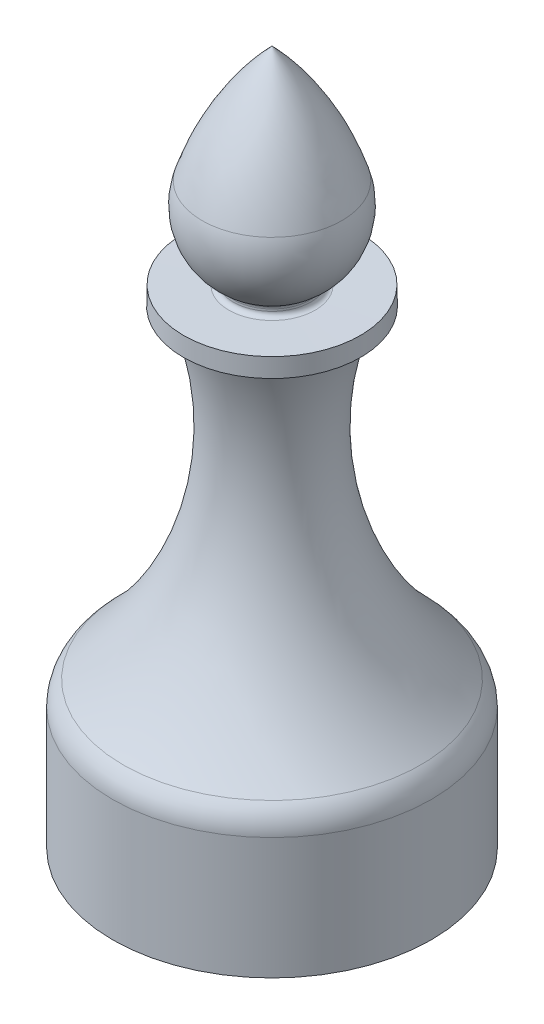
SolidWorks part; units mm, degrees
ref_plane "Front Plane" through (0, 0, 0) normal (0, 0, 1) x (1, 0, 0)
ref_plane "Top Plane" through (0, 0, 0) normal (0, 1, 0) x (1, 0, 0)
ref_plane "Right Plane" through (0, 0, 0) normal (1, 0, 0) x (0, 0, -1)
sketch "Sketch1" plane through (0, 0, 0) normal (0, 0, 1) x (1, 0, 0)
  line L0 (-45.1214, 61) -> (64.5343, 61) construction
  line L1 (0, 0) -> (14, 0)
  line L7 (0, 61) -> (0, 0)
  line L8 (14, 0) -> (14, 12)
  line L9 (0, 27.1439) -> (8.5958, 14.8679)
  line L10 (9.5, 12) -> (9.5, 0)
  line L11 (9.5, 12) -> (14, 12) construction
  arc A0 (14, 6.8598) -> (6.1449, 40.3453) centre (37.7288, 30.0902) cw construction
  arc A5 (6.1449, 40.3453) -> (14, 12) centre (31.4966, 32.1097) ccw
  arc A6 (8.5958, 14.8679) -> (9.5, 12) centre (4.5, 12) cw
  point P29 (9.5, 13.5765)
  line B0 (6.1449, 40.3453) -> (7.7914, 41.2078)
  line B1 (7.7914, 41.2078) -> (7.7647, 42.8586)
  line B2 (7.7647, 42.8586) -> (3.791, 42.7943)
  line B3 (3.3946, 43.2105) -> (3.3917, 43.3885)
  arc B4 (3.791, 42.7943) -> (3.3946, 43.2105) centre (3.8118, 43.2109) cw
  arc B5 (3.3917, 43.3885) -> (3.5324, 43.7095) centre (3.8128, 43.3953) cw
  arc B6 (3.5324, 43.7095) -> (6.1413, 50.7842) centre (0.2765, 48.9286) ccw
  arc B7 (6.1413, 50.7842) -> (0, 61) centre (-18.2787, 43.0578) ccw
  dimension "D9" = 5
  dimension "D1" = 61
  dimension "D2" = 14
  dimension "D3" = 12
  dimension "D5" = 9.5
  dimension "D8" = 145
sketch_block_instance "Block1-1"
sketch_block "Block1"
revolve "Revolve1" add sketch "Sketch1" angle 360 about L7
fillet "Fillet1" radius 3 1 edges at (0, 12, 14)
